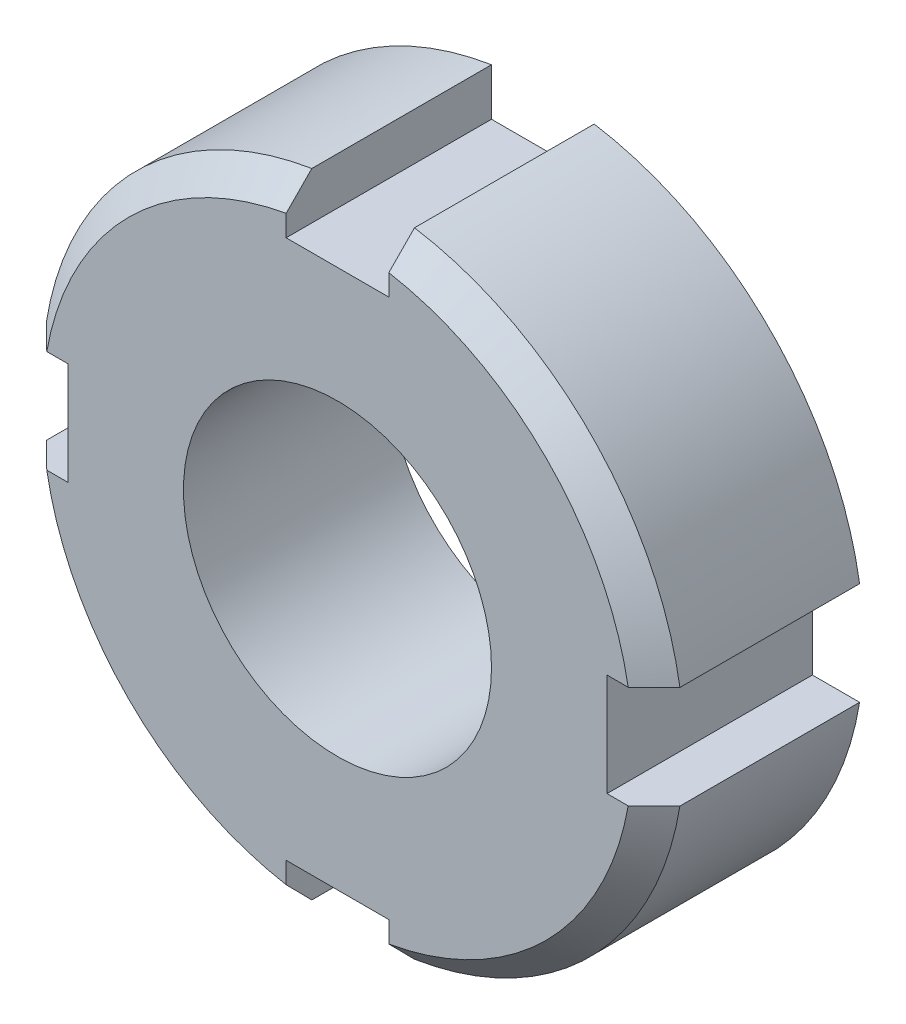
SolidWorks part; units mm, degrees
ref_plane "Front Plane" through (0, 0, 0) normal (0, 0, 1) x (1, 0, 0)
ref_plane "Top Plane" through (0, 0, 0) normal (0, 1, 0) x (1, 0, 0)
ref_plane "Right Plane" through (0, 0, 0) normal (1, 0, 0) x (0, 0, -1)
sketch "Sketch1" plane through (0, 0, 0) normal (0, 0, 1) x (1, 0, 0)
  circle A0 centre (0, 0) radius 12.5
  dimension "D1" = 25
extrude "Boss-Extrude1" add sketch "Sketch1" along normal blind 8
sketch "Sketch2" plane through (0, 0, 8) normal (0, 0, 1) x (1, 0, 0)
  circle A0 centre (0, 0) radius 6
  dimension "D1" = 12
extrude "Cut-Extrude1" cut sketch "Sketch2" against normal through all
sketch "Sketch3" plane through (0, 0, 8) normal (0, 0, 1) x (1, 0, 0)
  line L0 (0, 0) -> (0, 12.5) construction
  line L1 (0, 12.5) -> (-13.1398, 12.5) construction
  line L2 (10.5, 2) -> (14.5, 2)
  line L3 (-2, 10.5) -> (2, 10.5)
  line L4 (-2, 10.5) -> (-2, 14.5)
  line L5 (-2, 14.5) -> (2, 14.5)
  line L6 (2, 10.5) -> (2, 14.5)
  line L7 (-2, 10.5) -> (2, 14.5) construction
  line L8 (-2, 14.5) -> (2, 10.5) construction
  line L9 (10.5, 2) -> (10.5, -2)
  line L10 (10.5, -2) -> (14.5, -2)
  line L11 (14.5, 2) -> (14.5, -2)
  line L12 (2, -10.5) -> (2, -14.5)
  line L13 (2, -10.5) -> (-2, -10.5)
  line L14 (-2, -10.5) -> (-2, -14.5)
  line L15 (2, -14.5) -> (-2, -14.5)
  line L16 (-10.5, -2) -> (-14.5, -2)
  line L17 (-10.5, -2) -> (-10.5, 2)
  line L18 (-10.5, 2) -> (-14.5, 2)
  line L19 (-14.5, -2) -> (-14.5, 2)
  circle A0 centre (0, 0) radius 12.5 construction
  circle A1 centre (0, 0) radius 12.5 construction
  circle A2 centre (0, 0) radius 12.5 construction
  circle A3 centre (0, 0) radius 12.5 construction
  circle A4 centre (0, 0) radius 12.5 construction
  point P30 (0, 0)
  dimension "D1" = 4
  dimension "D2" = 2
  dimension "D3" = 4
extrude "Cut-Extrude2" cut sketch "Sketch3" against normal through all
chamfer "Chamfer1" distance 1 angle 45 4 edges at (-8.8388, -8.8388, 8) (8.8388, -8.8388, 8) (8.8388, 8.8388, 8) (-8.8388, 8.8388, 8)
equation "\"`\"=10"
